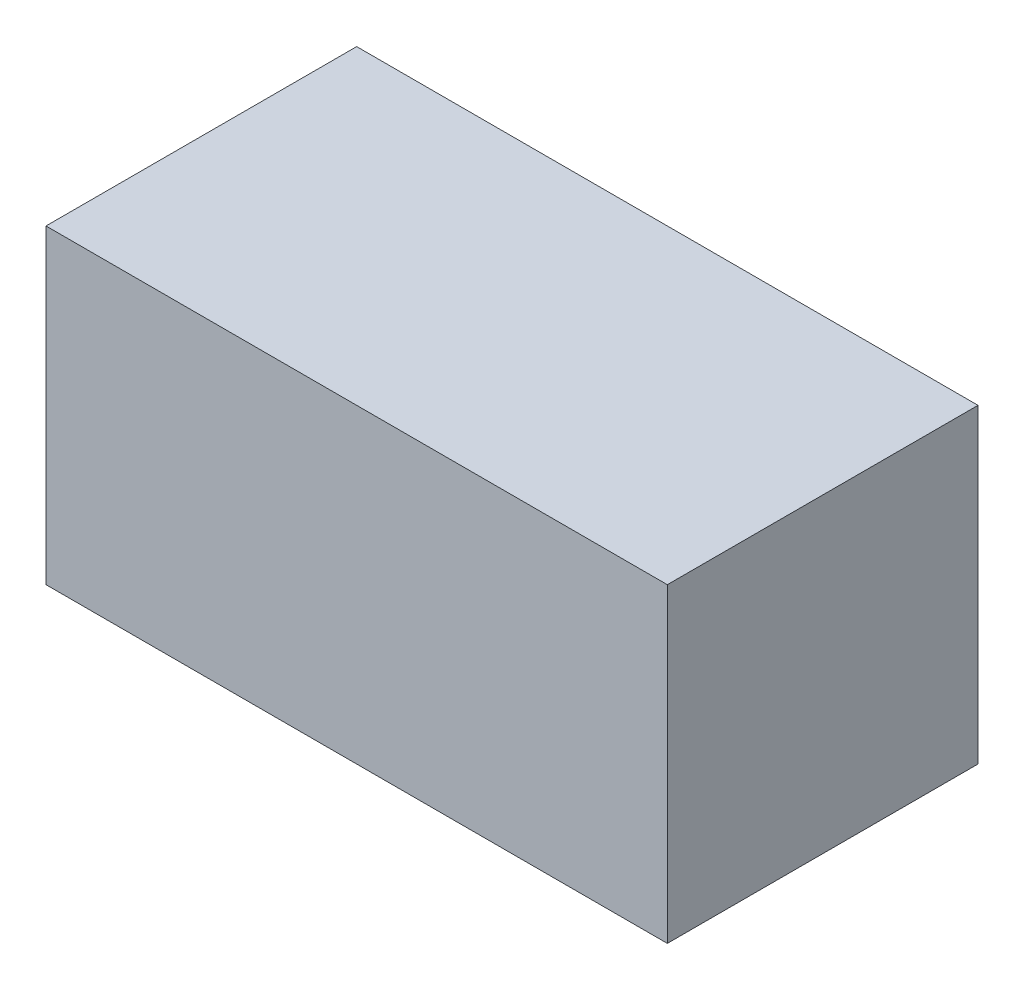
SolidWorks part; units mm, degrees
ref_plane "Front Plane" through (0, 0, 0) normal (0, 0, 1) x (1, 0, 0)
ref_plane "Top Plane" through (0, 0, 0) normal (0, 1, 0) x (1, 0, 0)
ref_plane "Right Plane" through (0, 0, 0) normal (1, 0, 0) x (0, 0, -1)
sketch "Sketch1" plane through (0, 0, 0) normal (0, 0, 1) x (1, 0, 0)
  line L0 (-12.7, 0) -> (-12.7, 3.175) construction
  line L1 (0, 0) -> (-25.4, 0)
  line L2 (0, 0) -> (0, 12.7)
  line L3 (0, 12.7) -> (-25.4, 12.7)
  line L4 (-25.4, 0) -> (-25.4, 12.7)
  line L5 (-12.7, 12.7) -> (-12.7, 9.525) construction
  line L6 (-25.4, 6.35) -> (-19.05, 6.35) construction
  line L7 (0, 6.35) -> (-6.35, 6.35) construction
  line L9 (-6.35, 3.175) -> (-19.05, 3.175)
  line L10 (-6.35, 3.175) -> (-6.35, 9.525)
  line L11 (-6.35, 9.525) -> (-19.05, 9.525)
  line L12 (-19.05, 3.175) -> (-19.05, 9.525)
  dimension "D1" = 25.4
  dimension "D2" = 12.7
  dimension "D3" = 12.7
  dimension "D4" = 6.35
extrude "Boss-Extrude1" add sketch "Sketch1" along normal blind 12.7
sketch "Sketch2" plane through (0, 0, 12.7) normal (0, 0, 1) x (1, 0, 0)
  line L1 (-6.35, 3.175) -> (-19.05, 3.175)
  line L2 (-6.35, 3.175) -> (-6.35, 9.525)
  line L3 (-6.35, 9.525) -> (-19.05, 9.525)
  line L4 (-19.05, 3.175) -> (-19.05, 9.525)
extrude "Boss-Extrude2" add sketch "Sketch2" against normal blind 6.35
